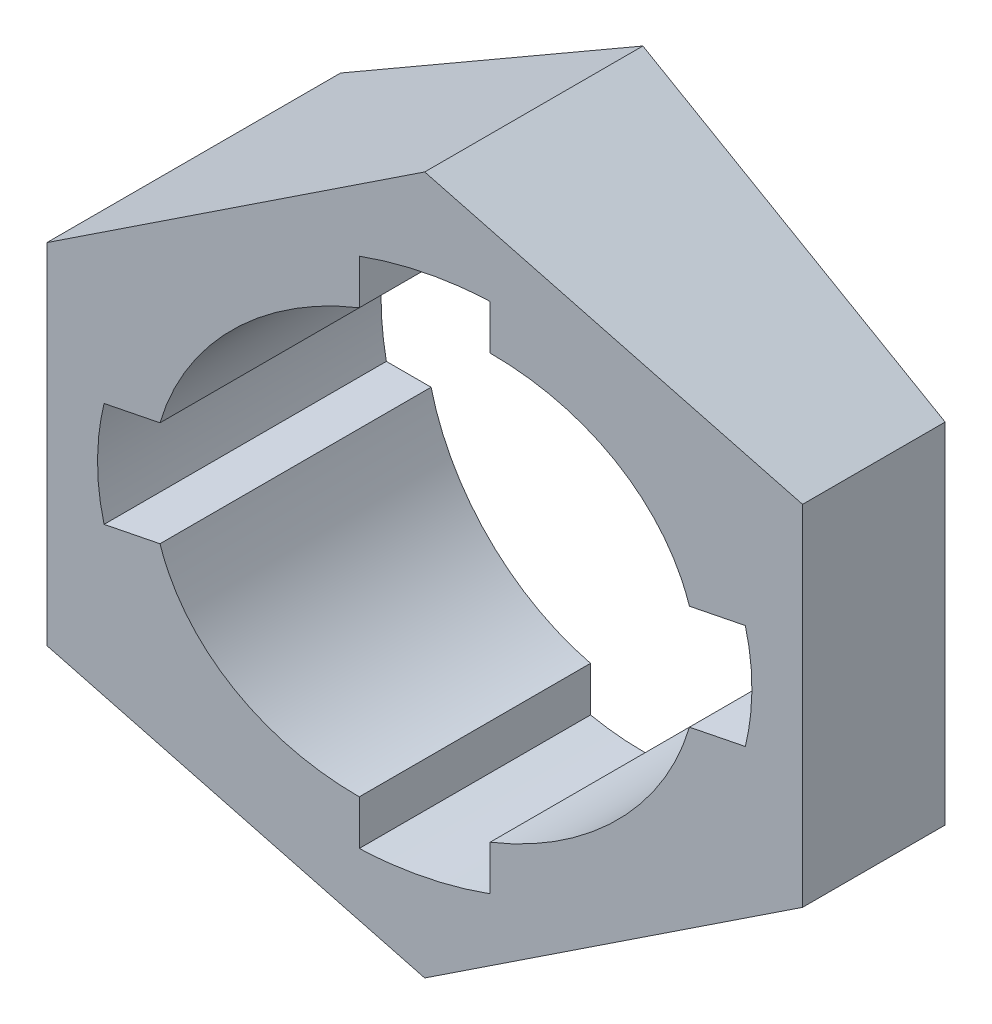
SolidWorks part; units mm, degrees
ref_plane "Front Plane" through (0, 0, 0) normal (0, 0, 1) x (1, 0, 0)
ref_plane "Top Plane" through (0, 0, 0) normal (0, 1, 0) x (1, 0, 0)
ref_plane "Right Plane" through (0, 0, 0) normal (1, 0, 0) x (0, 0, -1)
sketch "Sketch1" plane through (0, 0, 0) normal (0, 0, 1) x (1, 0, 0)
  line L1 (-80, 0) -> (0, 0)
  line L2 (-80, 0) -> (-80, 80)
  line L3 (-80, 80) -> (0, 80)
  line L4 (0, 0) -> (0, 80)
  point P4 (0, 0)
  dimension "D1" = 80
  dimension "D2" = 80
extrude "Boss-Extrude1" add sketch "Sketch1" along normal blind 35
sketch "Sketch4" plane through (0, 0, 0) normal (0, -1, 0) x (1, 0, 0)
  line L0 (-80, 35) -> (0, 15)
  line L1 (0, 35) -> (0, 0) construction
  line L2 (-80, 35) -> (0, 35)
  line L3 (-80, 35) -> (0, 35) construction
  line L4 (0, 35) -> (0, 15)
  line L7 (-80, 0) -> (0, 0) construction
  point P8 (0, 23.4977)
  dimension "D2" = 15
extrude "Cut-Extrude1" cut sketch "Sketch4" against normal up to next
sketch "Sketch5" plane through (0, 0, 0) normal (0, 0, -1) x (-1, 0, 0)
  line L0 (0, 80) -> (80, 80) construction
  line L1 (40, 80) -> (5.359, 60)
  line L2 (5.359, 60) -> (5.359, 20)
  line L3 (5.359, 20) -> (40, 0)
  line L4 (40, 0) -> (74.641, 20)
  line L5 (74.641, 20) -> (74.641, 60)
  line L6 (74.641, 60) -> (40, 80)
  line L7 (80, 0) -> (0, 0) construction
  line L8 (34, 69.3939) -> (34, 64.2693)
  line L9 (46, 69.3939) -> (46, 64.2693)
  line L10 (69.3939, 46) -> (64.2693, 46)
  line L11 (69.3939, 34) -> (64.2693, 34)
  line L12 (46, 10.6061) -> (46, 15.7307)
  line L13 (34, 10.6061) -> (34, 15.7307)
  line L14 (10.6061, 34) -> (15.7307, 34)
  line L15 (10.6061, 46) -> (15.7307, 46)
  line L16 (0, 80) -> (40, 80)
  line L17 (5.359, 60) -> (5.359, 20)
  line L18 (0, 80) -> (0, 0)
  line L19 (0, 0) -> (40, 0)
  line L20 (80, 0) -> (80, 80)
  line L21 (80, 80) -> (40, 80)
  arc A0 (15.7307, 34) -> (34, 15.7307) centre (40, 40) ccw
  arc A1 (46, 69.3939) -> (34, 69.3939) centre (40, 40) ccw
  arc A2 (69.3939, 34) -> (69.3939, 46) centre (40, 40) ccw
  arc A3 (34, 10.6061) -> (46, 10.6061) centre (40, 40) ccw
  arc A4 (10.6061, 46) -> (10.6061, 34) centre (40, 40) ccw
  arc A5 (64.2693, 46) -> (46, 64.2693) centre (40, 40) ccw
  arc A6 (46, 15.7307) -> (64.2693, 34) centre (40, 40) ccw
  arc A7 (34, 64.2693) -> (15.7307, 46) centre (40, 40) ccw
  point P31 (40, 40)
  line M23 (80, 0) -> (80, 80)
  line M24 (80, 80) -> (0, 80)
  line M25 (0, 80) -> (0, 0)
  line M26 (0, 0) -> (80, 0)
  dimension "D2" = 50
  dimension "D3" = 60
  dimension "D1" = 80
  dimension "D4" = 12
  dimension "D5" = 6
  dimension "D7" = 40
  dimension "D6" = 4
extrude "Cut-Extrude2" cut sketch "Sketch5" against normal blind 35 contours L8 A7 L15 A4 L14 A0 L13 A3 L12 A6 L11 A2 L10 A5 L9 A1 | L3 L2 L1 M24 M25 M26 | L6 L5 L4 M26 M23 M24
